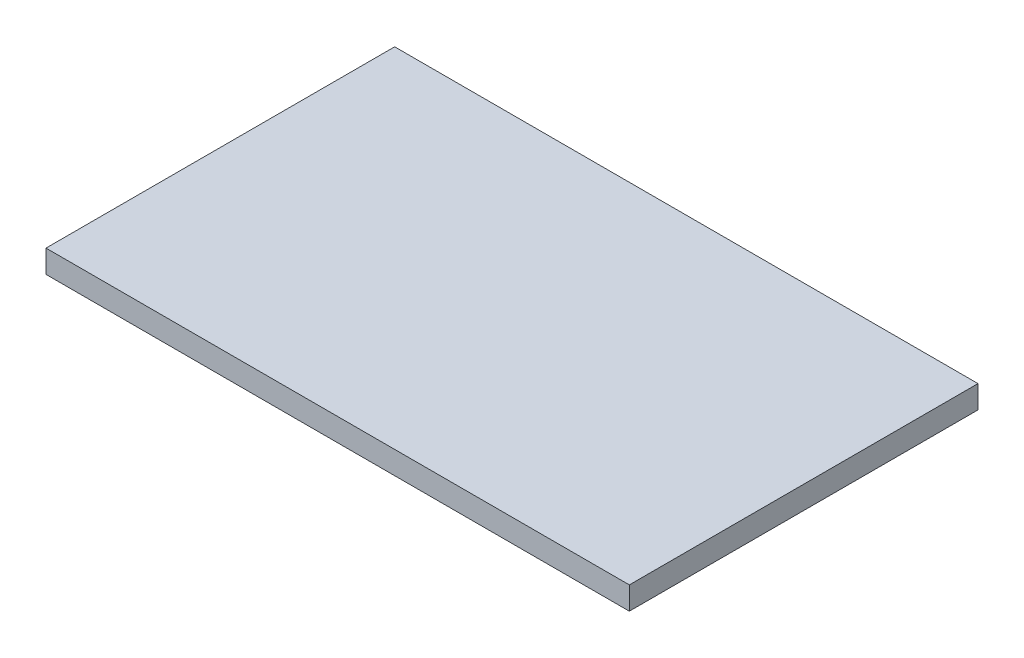
SolidWorks part; units mm, degrees
ref_plane "Front" through (0, 0, 0) normal (0, 0, 1) x (1, 0, 0)
ref_plane "Top" through (0, 0, 0) normal (0, 1, 0) x (1, 0, 0)
ref_plane "Right" through (0, 0, 0) normal (1, 0, 0) x (0, 0, -1)
sketch "Esquisse1" plane through (0, 0, 0) normal (0, 1, 0) x (1, 0, 0)
  line L1 (0, 0) -> (51.1514, 0)
  line L2 (0, 0) -> (0, 30.5733)
  line L3 (0, 30.5733) -> (51.1514, 30.5733)
  line L4 (51.1514, 0) -> (51.1514, 30.5733)
extrude "Boss.-Extru.1" add sketch "Esquisse1" along normal blind 2
